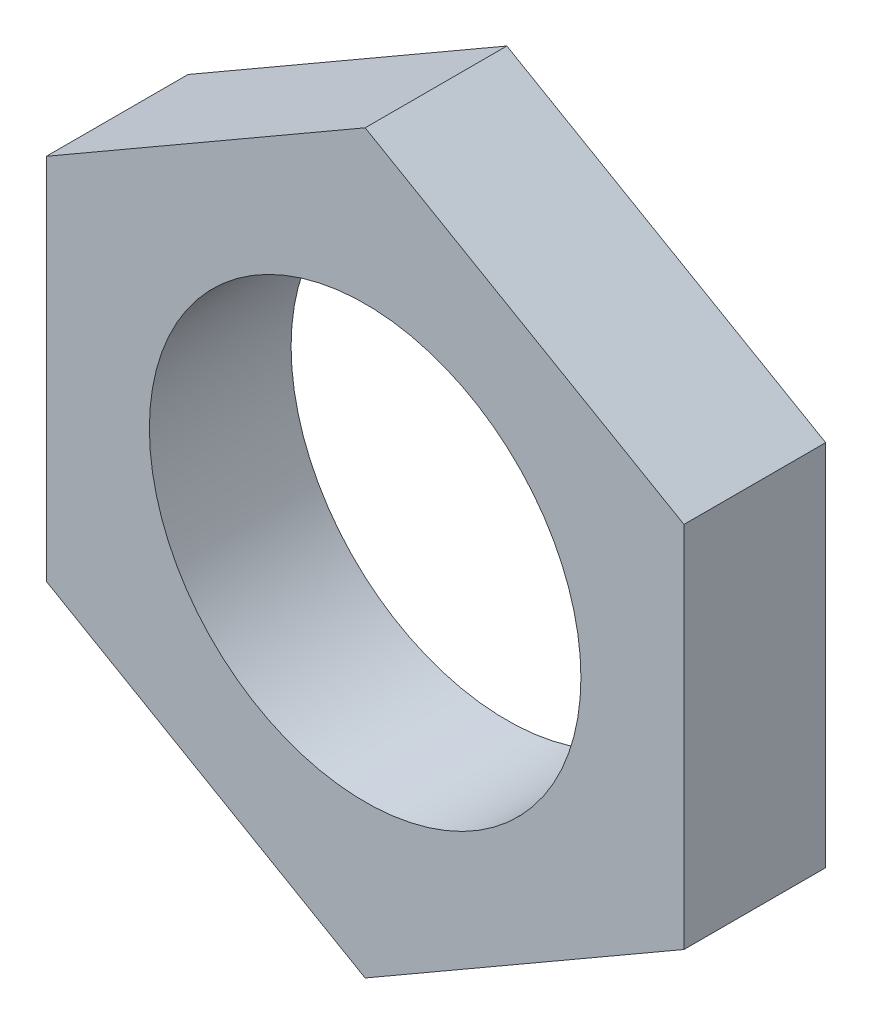
SolidWorks part; units mm, degrees
ref_plane "前视基准面" through (0, 0, 0) normal (0, 0, 1) x (1, 0, 0)
ref_plane "上视基准面" through (0, 0, 0) normal (0, 1, 0) x (1, 0, 0)
ref_plane "右视基准面" through (0, 0, 0) normal (1, 0, 0) x (0, 0, -1)
other "Configuration Table"
sketch "草图1" plane through (0, 0, 0) normal (0, 0, 1) x (1, 0, 0)
  line L1 (0, 5.7158) -> (-4.95, 2.8579)
  line L2 (-4.95, 2.8579) -> (-4.95, -2.8579)
  line L3 (-4.95, -2.8579) -> (0, -5.7158)
  line L4 (0, -5.7158) -> (4.95, -2.8579)
  line L5 (4.95, -2.8579) -> (4.95, 2.8579)
  line L6 (4.95, 2.8579) -> (0, 5.7158)
  circle A0 centre (0, 0) radius 4.95 construction
  circle A1 centre (0, 0) radius 3.35
  dimension "D2" = 6.7
  dimension "D1" = 9.9
extrude "凸台-拉伸1" add sketch "草图1" along normal blind 2.2
cosmetic thread "装饰螺纹线1"
